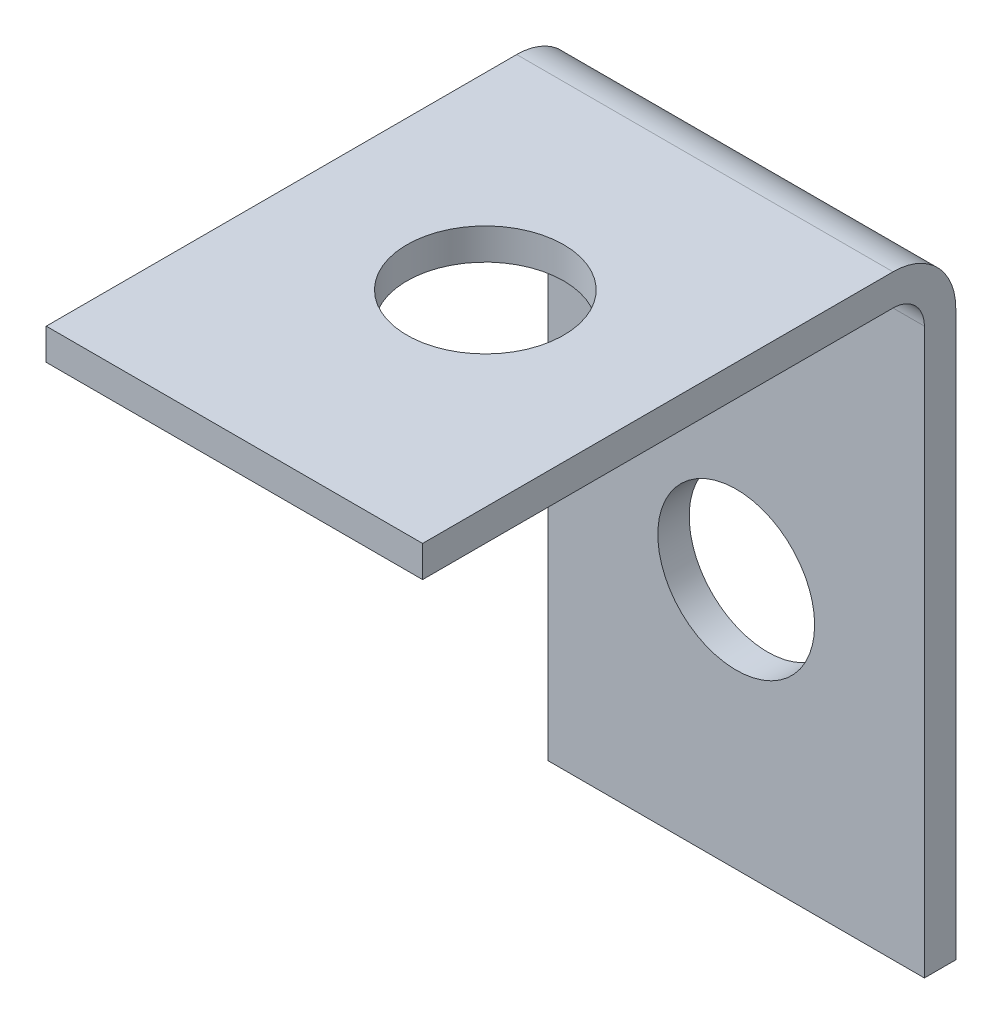
SolidWorks part; units mm, degrees
ref_plane "Alzado" through (0, 0, 0) normal (0, 0, 1) x (1, 0, 0)
ref_plane "Planta" through (0, 0, 0) normal (0, 1, 0) x (1, 0, 0)
ref_plane "Vista lateral" through (0, 0, 0) normal (1, 0, 0) x (0, 0, -1)
sketch "Croquis1" plane through (0, 0, 0) normal (0, 0, 1) x (1, 0, 0)
  line L0 (0, 0) -> (0, -12) construction
  line L1 (0, -12) -> (0, -20) construction
  line L2 (0, 0) -> (6, 0) construction
  line L3 (0, -20) -> (-6, -20) construction
  line L5 (6, 0) -> (-6, 0)
  line L6 (6, 0) -> (6, -20)
  line L7 (6, -20) -> (-6, -20)
  line L8 (-6, 0) -> (-6, -20)
  circle A0 centre (0, -12) radius 2.5
  dimension "D2" = 5
  dimension "D1" = 12
  dimension "D3" = 8
  dimension "D4" = 6
  dimension "D5" = 6
extrude "Saliente-Extruir1" add sketch "Croquis1" along normal blind 1
sketch "Croquis2" plane through (0, 0, 1) normal (0, 0, 1) x (1, 0, 0)
  line L0 (6, -20) -> (6, 0) construction
  line L1 (-6, 0) -> (6, 0)
  line L2 (-6, 0) -> (-6, -1)
  line L3 (-6, -1) -> (6, -1)
  line L4 (6, 0) -> (6, -1)
  dimension "D1" = 1
extrude "Saliente-Extruir2" add sketch "Croquis2" along normal blind 16
sketch "Croquis3" plane through (0, -1, 0) normal (0, -1, 0) x (1, 0, 0)
  line L0 (0, 17) -> (0, 9) construction
  line L1 (-6, 17) -> (6, 17) construction
  circle A0 centre (0, 9) radius 2.5
  dimension "D2" = 5
  dimension "D1" = 8
extrude "Cortar-Extruir1" cut sketch "Croquis3" against normal blind 8
fillet "Redondeo2" radius 1 1 edges at (0, -1, 1)
fillet "Redondeo3" radius 2 1 edges at (0, 0, 0)
